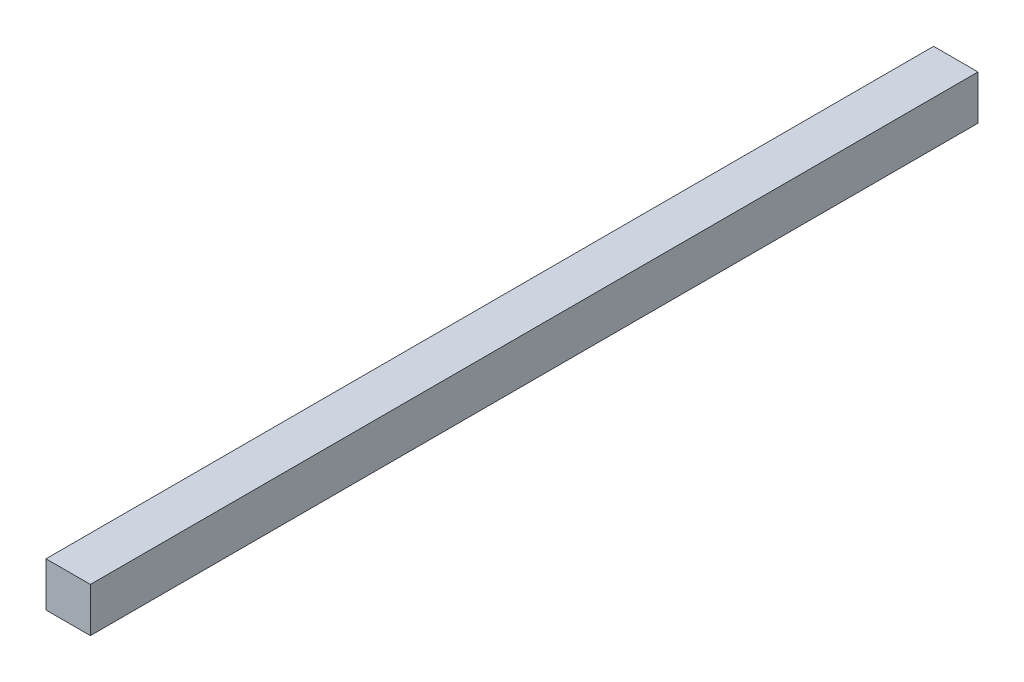
SolidWorks part; units mm, degrees
ref_plane "前视基准面" through (0, 0, 0) normal (0, 0, 1) x (1, 0, 0)
ref_plane "上视基准面" through (0, 0, 0) normal (0, 1, 0) x (1, 0, 0)
ref_plane "右视基准面" through (0, 0, 0) normal (1, 0, 0) x (0, 0, -1)
sketch "草图1" plane through (0, 0, 0) normal (0, 0, 1) x (1, 0, 0)
  line L1 (-15, -15) -> (15, -15)
  line L2 (-15, -15) -> (-15, 15)
  line L3 (-15, 15) -> (15, 15)
  line L4 (15, -15) -> (15, 15)
  line L5 (-15, -15) -> (15, 15) construction
  line L6 (-15, 15) -> (15, -15) construction
  point P0 (0, 0)
  dimension "D1" = 30
extrude "凸台-拉伸1" add sketch "草图1" along normal blind 600
